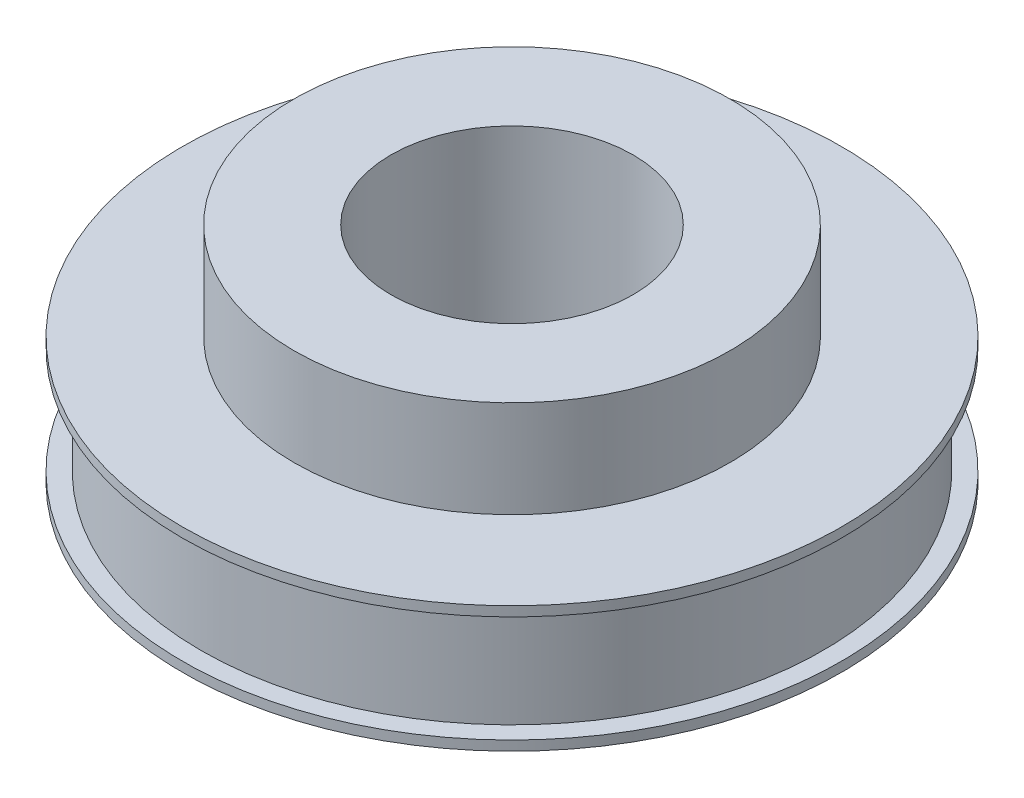
SolidWorks part; units mm, degrees
ref_plane "前视基准面" through (0, 0, 0) normal (0, 0, 1) x (1, 0, 0)
ref_plane "上视基准面" through (0, 0, 0) normal (0, 1, 0) x (1, 0, 0)
ref_plane "右视基准面" through (0, 0, 0) normal (1, 0, 0) x (0, 0, -1)
other "Configuration Table"
sketch "草图1" plane through (0, 0, 0) normal (0, 1, 0) x (1, 0, 0)
  circle A0 centre (0, 0) radius 32.085
  dimension "D1" = 64.17
extrude "凸台-拉伸1" add sketch "草图1" along normal blind 11
sketch "草图2" plane through (0, 11, 0) normal (0, 1, 0) x (1, 0, 0)
  circle A0 centre (0, 0) radius 34
  dimension "D1" = 68
extrude "凸台-拉伸2" add sketch "草图2" along normal blind 1
sketch "草图3" plane through (0, 0, 0) normal (0, -1, 0) x (1, 0, 0)
  circle A1 centre (0, 0) radius 34
  circle A2 centre (0, 0) radius 34
  dimension "D1" = 0
extrude "凸台-拉伸3" add sketch "草图3" along normal blind 1
sketch "草图4" plane through (0, 12, 0) normal (0, 1, 0) x (1, 0, 0)
  circle A0 centre (0, 0) radius 12.5
  dimension "D1" = 25
extrude "切除-拉伸1" cut sketch "草图4" against normal through all
sketch "草图5" plane through (0, 12, 0) normal (0, 1, 0) x (1, 0, 0)
  circle A0 centre (0, 0) radius 12.5
  circle A1 centre (0, 0) radius 22.5
  dimension "D1" = 45
extrude "凸台-拉伸4" add sketch "草图5" along normal blind 10
